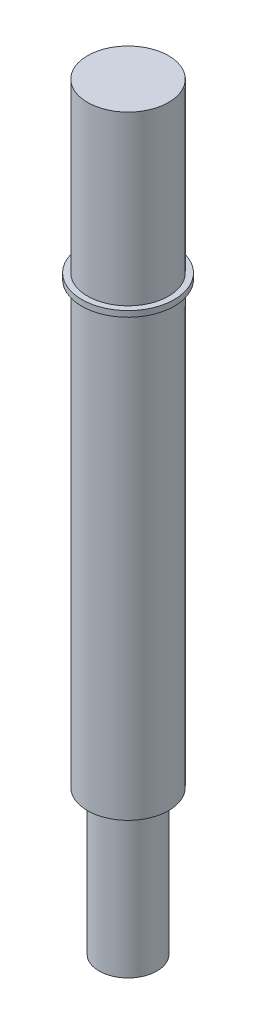
SolidWorks part; units mm, degrees
ref_plane "Front Plane" through (0, 0, 0) normal (0, 0, 1) x (1, 0, 0)
ref_plane "Top Plane" through (0, 0, 0) normal (0, 1, 0) x (1, 0, 0)
ref_plane "Right Plane" through (0, 0, 0) normal (1, 0, 0) x (0, 0, -1)
sketch "Sketch1" plane through (0, 0, 0) normal (0, 0, 1) x (1, 0, 0)
  line L0 (0, 0) -> (1.778, 0)
  line L1 (1.778, 0) -> (1.778, -26.924)
  line L2 (1.778, -26.924) -> (1.27, -26.924)
  line L3 (1.27, -26.924) -> (1.27, -33.274)
  line L4 (1.27, -33.274) -> (0, -33.274)
  line L5 (0, -33.274) -> (0, 0)
  line L6 (1.778, -7.366) -> (2.032, -7.366)
  line L7 (2.032, -7.366) -> (2.032, -7.62)
  line L8 (2.032, -7.62) -> (1.778, -7.62)
  line L9 (0, 0) -> (0, 14.3765) construction
  dimension "D1" = 1.778
  dimension "D2" = 33.274
  dimension "D3" = 26.924
  dimension "D4" = 1.27
  dimension "D5" = 7.62
  dimension "D6" = 0.254
revolve "Revolve2" add sketch "Sketch1" angle 360 about L9
